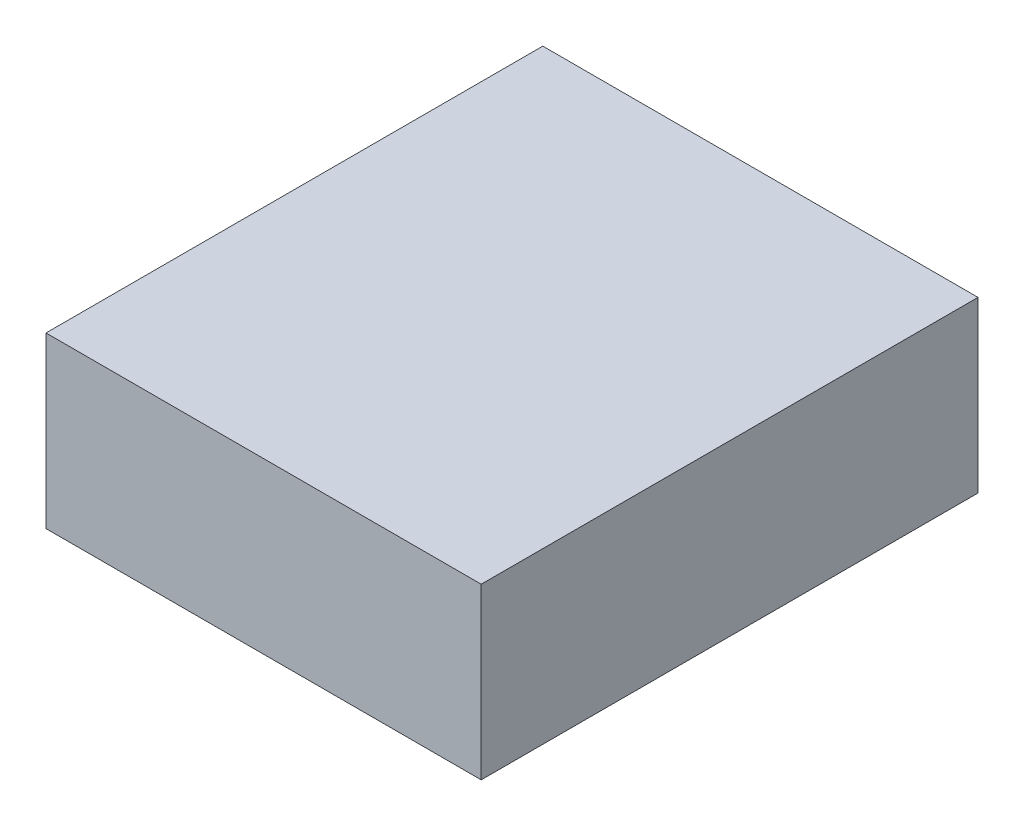
SolidWorks part; units mm, degrees
material "cpu"
ref_plane "Alzado" through (0, 0, 0) normal (0, 0, 1) x (1, 0, 0)
ref_plane "Planta" through (0, 0, 0) normal (0, 1, 0) x (1, 0, 0)
ref_plane "Vista lateral" through (0, 0, 0) normal (1, 0, 0) x (0, 0, -1)
sketch "Croquis1" plane through (0, 0, 0) normal (0, 1, 0) x (1, 0, 0)
  line L1 (28.25, -32.25) -> (-28.25, -32.25)
  line L2 (28.25, -32.25) -> (28.25, 32.25)
  line L3 (28.25, 32.25) -> (-28.25, 32.25)
  line L4 (-28.25, -32.25) -> (-28.25, 32.25)
  line L5 (28.25, -32.25) -> (-28.25, 32.25) construction
  line L6 (28.25, 32.25) -> (-28.25, -32.25) construction
  point P0 (0, 0)
  dimension "D1" = 64.5
  dimension "D2" = 56.5
extrude "Saliente-Extruir1" add sketch "Croquis1" along normal blind 22
